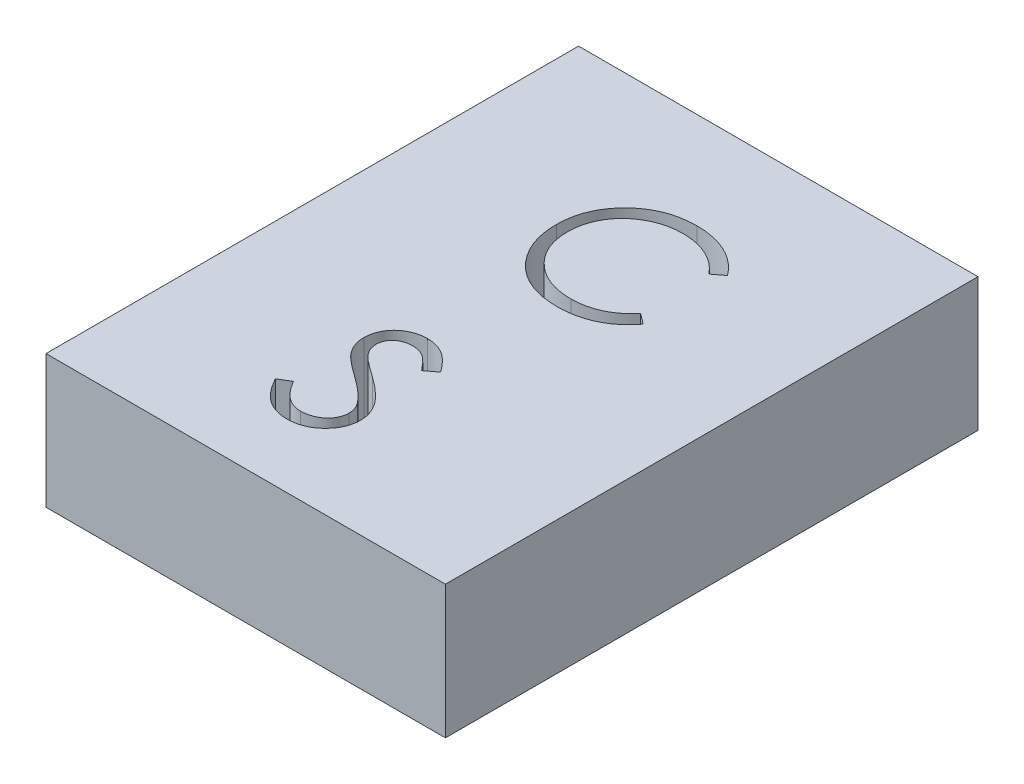
SolidWorks part; units mm, degrees
ref_plane "Front Plane" through (0, 0, 0) normal (0, 0, 1) x (1, 0, 0)
ref_plane "Top Plane" through (0, 0, 0) normal (0, 1, 0) x (1, 0, 0)
ref_plane "Right Plane" through (0, 0, 0) normal (1, 0, 0) x (0, 0, -1)
sketch "Sketch1" plane through (0, 0, 0) normal (0, 1, 0) x (1, 0, 0)
  line L1 (0, 0) -> (38.1, 0)
  line L2 (0, 0) -> (0, 50.8)
  line L3 (0, 50.8) -> (38.1, 50.8)
  line L4 (38.1, 0) -> (38.1, 50.8)
  dimension "D1" = 38.1
  dimension "D2" = 50.8
extrude "Boss-Extrude1" add sketch "Sketch1" along normal blind 12.7
sketch "Sketch2" plane through (0, 12.7, 0) normal (0, 1, 0) x (1, 0, 0)
  line L0 (38.1, 50.8) -> (0, 50.8) construction
  line L1 (38.1, 0) -> (38.1, 50.8) construction
  text T0 "C\r\nS" font "Century Gothic" height in points 48
  dimension "D1" = 22.225
  dimension "D2" = 25.4
extrude "Cut-Extrude1" cut sketch "Sketch2" against normal through all
